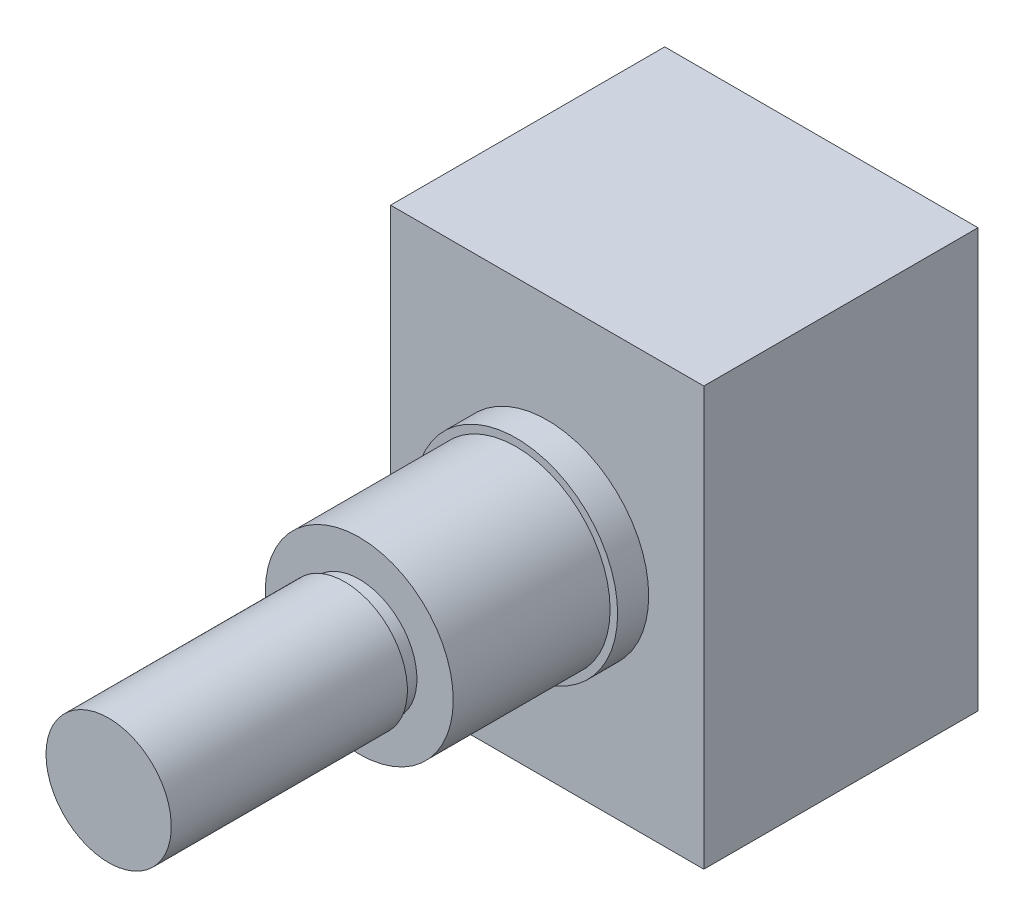
SolidWorks part; units mm, degrees
ref_plane "Front Plane" through (0, 0, 0) normal (0, 0, 1) x (1, 0, 0)
ref_plane "Top Plane" through (0, 0, 0) normal (0, 1, 0) x (1, 0, 0)
ref_plane "Right Plane" through (0, 0, 0) normal (1, 0, 0) x (0, 0, -1)
ref_plane "Plane1" through (0, 0, 13.8938) normal (0, 0, 1) x (1, 0, 0)
sketch "Sketch1" plane through (0, 0, 13.8938) normal (0, 0, 1) x (1, 0, 0)
  line L0 (7.9375, -10.6045) -> (7.9375, 10.6045)
  line L1 (7.9375, 10.6045) -> (-7.9375, 10.6045)
  line L2 (-7.9375, 10.6045) -> (-7.9375, -10.6045)
  line L3 (-7.9375, -10.6045) -> (7.9375, -10.6045)
extrude "Boss-Extrude1" add sketch "Sketch1" against normal blind 13.8938
ref_plane "Plane2" through (0, 0, 0) normal (0, -1, 0) x (1, 0, 0)
sketch "Sketch2" plane through (0, 0, 0) normal (0, -1, 0) x (1, 0, 0)
  line L0 (3.175, 36.1188) -> (0, 36.1188)
  line L1 (0, 36.1188) -> (0, 13.8938)
  line L2 (0, 13.8938) -> (5.1435, 13.8938)
  line L3 (5.1435, 13.8938) -> (5.1435, 15.4686)
  line L4 (5.1435, 15.4686) -> (4.7625, 15.4686)
  line L5 (4.7625, 15.4686) -> (4.7625, 23.4188)
  line L6 (4.7625, 23.4188) -> (2.921, 23.4188)
  line L7 (2.921, 23.4188) -> (2.921, 24.1554)
  line L8 (2.921, 24.1554) -> (3.175, 24.1554)
  line L9 (3.175, 24.1554) -> (3.175, 36.1188)
  line L10 (0, 36.1188) -> (0, 13.8938) construction
revolve "Revolve1" add sketch "Sketch2" angle 360 about L10
